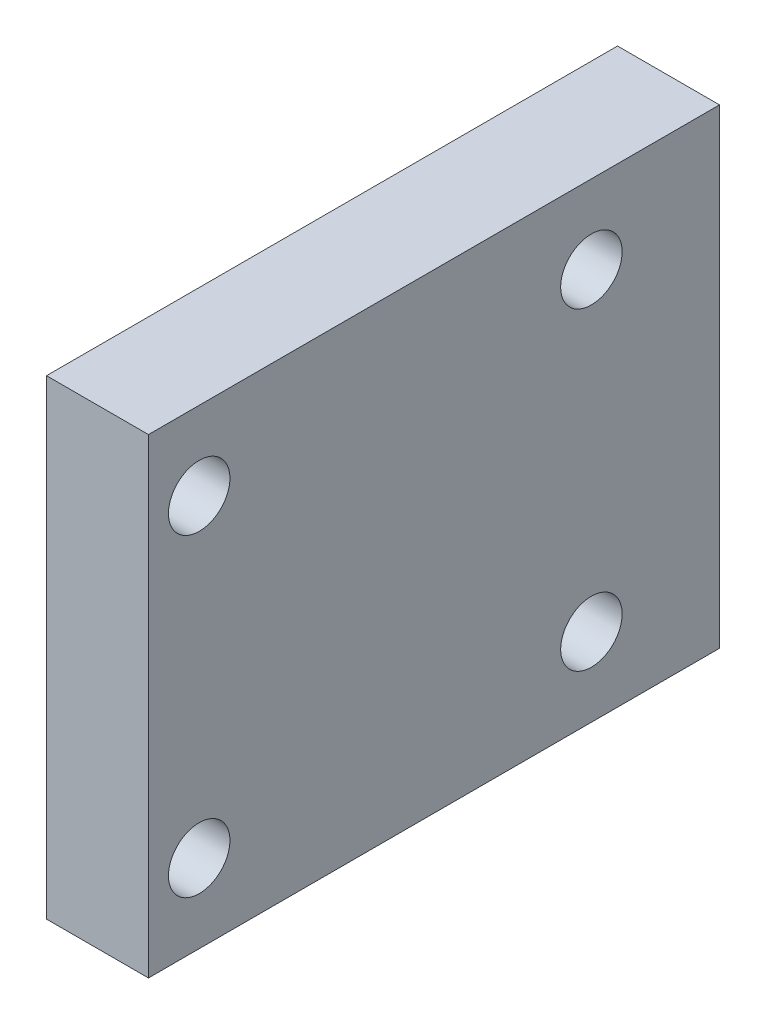
SolidWorks part; units mm, degrees
ref_plane "Front Plane" through (0, 0, 0) normal (0, 0, 1) x (1, 0, 0)
ref_plane "Top Plane" through (0, 0, 0) normal (0, 1, 0) x (1, 0, 0)
ref_plane "Right Plane" through (0, 0, 0) normal (1, 0, 0) x (0, 0, -1)
sketch "Sketch2" plane through (-488.9654, 0, 0) normal (1, 0, 0) x (0, 0, -1)
  line L1 (194.9873, 128.4838) -> (194.9873, 166.5838)
  line L2 (194.9873, 126.5338) -> (194.9873, 131.5338) construction
  line L3 (229.0661, 128.4838) -> (140.1661, 128.4838) construction
  line L4 (194.9873, 167.5338) -> (194.9873, 165.7338) construction
  line L5 (140.1661, 166.5838) -> (229.0661, 166.5838) construction
  line L6 (194.9873, 166.5838) -> (148.7593, 166.5838)
  line L7 (148.7593, 166.5838) -> (148.7593, 128.4838)
  line L8 (194.9873, 128.4838) -> (148.7593, 128.4838)
  dimension "D1" = 46.228
extrude "Boss-Extrude1" add sketch "Sketch2" along normal blind 8.255
hole_wizard "#10 Clearance Hole1" positions "Sketch3" profile "Sketch4" hole size "#10" standard "ANSI Inch"
sketch "Sketch3" plane through (-488.9654, 0, 0) normal (-1, 0, 0) x (0, 0, 1)
  point P0 (-184.6161, 160.2338)
  point P3 (-152.8661, 160.2338)
  point P6 (-152.8661, 134.8338)
  point P9 (-184.6161, 134.8338)
  point P15 (0, 0)
sketch "Sketch4" plane through (-488.9654, 160.2338, -184.6161) normal (0, 1, 0) x (0, 0, 1)
  line L0 (0, 0) -> (0, 26.8957)
  line L1 (0, 26.8957) -> (2.4892, 25.4)
  line L2 (2.4892, 25.4) -> (2.4892, 0)
  line L5 (2.4892, 0) -> (0, 0)
  line L10 (0, 26.8957) -> (-2.4892, 25.4) construction
  line L11 (0, -6.35) -> (0, 107.95) construction
  dimension "Hole Dia." = 4.9784
  dimension "Hole Depth" = 25.4
  dimension "Drill Angle" = 118
